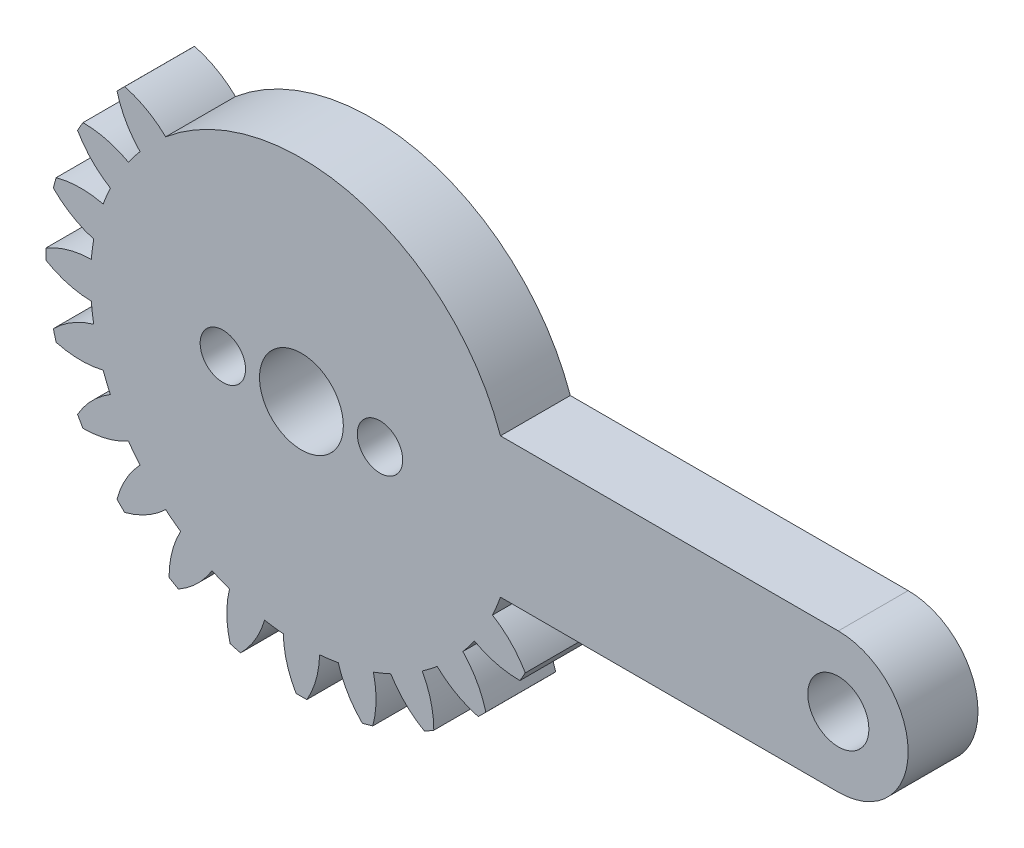
SolidWorks part; units mm, degrees
ref_plane "Front Plane" through (0, 0, 0) normal (0, 0, 1) x (1, 0, 0)
ref_plane "Top Plane" through (0, 0, 0) normal (0, 1, 0) x (1, 0, 0)
ref_plane "Right Plane" through (0, 0, 0) normal (1, 0, 0) x (0, 0, -1)
sketch "Sketch1" plane through (0, 0, 0) normal (0, 0, 1) x (1, 0, 0)
  line L0 (0, 0) -> (0, 14.63) construction
  line L1 (0, 0) -> (30.75, 0) construction
  line L2 (11.3985, 4) -> (30.75, 4)
  line L4 (30.75, -4) -> (11.3985, -4)
  circle A0 centre (0, 0) radius 1.75
  circle A1 centre (0, 0) radius 12.08
  circle A2 centre (0, 0) radius 14.63
  arc A3 (0.31, 14.6267) -> (1.04, 12.0351) centre (-4.3586, 11.913) cw
  arc A4 (-0.31, 14.6267) -> (-1.04, 12.0351) centre (4.3586, 11.913) ccw
  arc A5 (4.0851, 14.0481) -> (4.1195, 11.3559) centre (-1.1268, 12.6352) cw
  arc A6 (3.4862, 14.2086) -> (2.1104, 11.8942) centre (7.2934, 10.379) ccw
  arc A7 (7.5818, 12.5121) -> (6.9182, 9.9027) centre (2.1818, 12.4963) cw
  arc A8 (7.0449, 12.8221) -> (5.1169, 10.9427) centre (9.7312, 8.1377) ccw
  arc A9 (10.5619, 10.1234) -> (9.2455, 7.7747) centre (5.3418, 11.5058) cw
  arc A10 (10.1234, 10.5619) -> (7.7747, 9.2455) centre (11.5058, 5.3418) ccw
  arc A11 (12.8221, 7.0449) -> (10.9427, 5.1169) centre (8.1377, 9.7312) cw
  arc A12 (12.5121, 7.5818) -> (9.9027, 6.9182) centre (12.4963, 2.1818) ccw
  arc A13 (14.2086, 3.4862) -> (11.8942, 2.1104) centre (10.379, 7.2934) cw
  arc A14 (14.0481, 4.0851) -> (11.3559, 4.1195) centre (12.6352, -1.1268) ccw
  arc A15 (14.6267, -0.31) -> (12.0351, -1.04) centre (11.913, 4.3586) cw
  arc A16 (14.6267, 0.31) -> (12.0351, 1.04) centre (11.913, -4.3586) ccw
  arc A17 (14.0481, -4.0851) -> (11.3559, -4.1195) centre (12.6352, 1.1268) cw
  arc A18 (14.2086, -3.4862) -> (11.8942, -2.1104) centre (10.379, -7.2934) ccw
  arc A19 (12.5121, -7.5818) -> (9.9027, -6.9182) centre (12.4963, -2.1818) cw
  arc A20 (12.8221, -7.0449) -> (10.9427, -5.1169) centre (8.1377, -9.7312) ccw
  arc A21 (10.1234, -10.5619) -> (7.7747, -9.2455) centre (11.5058, -5.3418) cw
  arc A22 (10.5619, -10.1234) -> (9.2455, -7.7747) centre (5.3418, -11.5058) ccw
  arc A23 (7.0449, -12.8221) -> (5.1169, -10.9427) centre (9.7312, -8.1377) cw
  arc A24 (7.5818, -12.5121) -> (6.9182, -9.9027) centre (2.1818, -12.4963) ccw
  arc A25 (3.4862, -14.2086) -> (2.1104, -11.8942) centre (7.2934, -10.379) cw
  arc A26 (4.0851, -14.0481) -> (4.1195, -11.3559) centre (-1.1268, -12.6352) ccw
  arc A27 (-0.31, -14.6267) -> (-1.04, -12.0351) centre (4.3586, -11.913) cw
  arc A28 (0.31, -14.6267) -> (1.04, -12.0351) centre (-4.3586, -11.913) ccw
  arc A29 (-4.0851, -14.0481) -> (-4.1195, -11.3559) centre (1.1268, -12.6352) cw
  arc A30 (-3.4862, -14.2086) -> (-2.1104, -11.8942) centre (-7.2934, -10.379) ccw
  arc A31 (-7.5818, -12.5121) -> (-6.9182, -9.9027) centre (-2.1818, -12.4963) cw
  arc A32 (-7.0449, -12.8221) -> (-5.1169, -10.9427) centre (-9.7312, -8.1377) ccw
  arc A33 (-10.5619, -10.1234) -> (-9.2455, -7.7747) centre (-5.3418, -11.5058) cw
  arc A34 (-10.1234, -10.5619) -> (-7.7747, -9.2455) centre (-11.5058, -5.3418) ccw
  arc A35 (-12.8221, -7.0449) -> (-10.9427, -5.1169) centre (-8.1377, -9.7312) cw
  arc A36 (-12.5121, -7.5818) -> (-9.9027, -6.9182) centre (-12.4963, -2.1818) ccw
  arc A37 (-14.2086, -3.4862) -> (-11.8942, -2.1104) centre (-10.379, -7.2934) cw
  arc A38 (-14.0481, -4.0851) -> (-11.3559, -4.1195) centre (-12.6352, 1.1268) ccw
  arc A39 (-14.6267, 0.31) -> (-12.0351, 1.04) centre (-11.913, -4.3586) cw
  arc A40 (-14.6267, -0.31) -> (-12.0351, -1.04) centre (-11.913, 4.3586) ccw
  arc A41 (-14.0481, 4.0851) -> (-11.3559, 4.1195) centre (-12.6352, -1.1268) cw
  arc A42 (-14.2086, 3.4862) -> (-11.8942, 2.1104) centre (-10.379, 7.2934) ccw
  arc A43 (-12.5121, 7.5818) -> (-9.9027, 6.9182) centre (-12.4963, 2.1818) cw
  arc A44 (-12.8221, 7.0449) -> (-10.9427, 5.1169) centre (-8.1377, 9.7312) ccw
  arc A45 (-10.1234, 10.5619) -> (-7.7747, 9.2455) centre (-11.5058, 5.3418) cw
  arc A46 (-10.5619, 10.1234) -> (-9.2455, 7.7747) centre (-5.3418, 11.5058) ccw
  arc A47 (-7.0449, 12.8221) -> (-5.1169, 10.9427) centre (-9.7312, 8.1377) cw
  arc A48 (-7.5818, 12.5121) -> (-6.9182, 9.9027) centre (-2.1818, 12.4963) ccw
  arc A49 (-3.4862, 14.2086) -> (-2.1104, 11.8942) centre (-7.2934, 10.379) cw
  arc A50 (-4.0851, 14.0481) -> (-4.1195, 11.3559) centre (1.1268, 12.6352) ccw
  arc A51 (30.75, 4) -> (30.75, -4) centre (30.75, 0) cw
  circle A52 centre (30.75, 0) radius 1.75
  arc A53 (-11.8942, 2.1104) -> (-11.3559, 4.1195) centre (0, 0) cw
  arc A54 (-14.2086, 3.4862) -> (-14.0481, 4.0851) centre (0, 0) cw
  point P153 (0, 0)
  dimension "D1" = 3.5
  dimension "D2" = 24.16
  dimension "D3" = 29.26
  dimension "D6" = 5.4
  dimension "D9" = 4
  dimension "D10" = 3.5
  dimension "D4" = 0.62
  dimension "D5" = 2.08
  dimension "D8" = 30.75
  dimension "D11" = 1.0796
  dimension "D7" = 24
extrude "Boss-Extrude3" add sketch "Sketch1" along normal blind 4 contours A16 A2 A13 A1 | A2 A16 A1 A15 | A18 A2 A15 A1 | A2 A18 A1 L4 | A2 A20 A1 A19 | A2 A22 A1 A21 | A2 A24 A1 A23 | A1 | A2 A26 A1 A25 | A2 A28 A1 A27 | A2 A30 A1 A29 | A2 A32 A1 A31 | A2 A34 A1 A33 | A2 A36 A1 A35 | A2 A38 A1 A37 | A2 A40 A1 A39 | A2 A42 A1 A41 | A2 A44 A1 A43 | A2 A46 A1 A45 | A13 A2 L2 A1 | A51 L2 A2 L4 A52
sketch "Sketch3" plane through (0, 0, 4) normal (0, 0, 1) x (1, 0, 0)
  line L0 (-4.5, 0) -> (4.5, 0) construction
  circle A0 centre (4.5, 0) radius 1.3
  circle A1 centre (-4.5, 0) radius 1.3
  circle A2 centre (0, 0) radius 2.4
  dimension "D3" = 2.6
  dimension "D4" = 4.8
  dimension "D1" = 9
  dimension "D2" = 4.5
extrude "Cut-Extrude1" cut sketch "Sketch3" against normal through all
